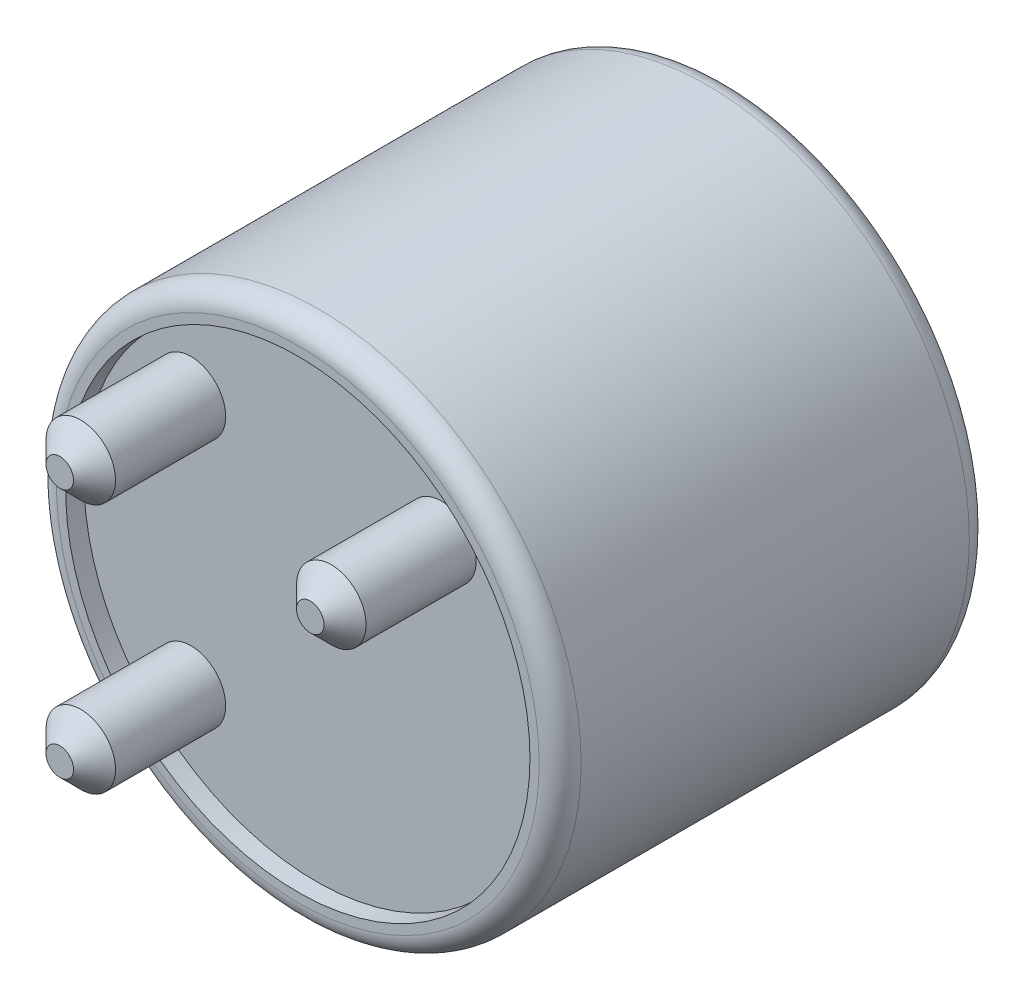
SolidWorks part; units mm, degrees
ref_plane "Спереди" through (0, 0, 0) normal (0, 0, 1) x (1, 0, 0)
ref_plane "Сверху" through (0, 0, 0) normal (0, 1, 0) x (1, 0, 0)
ref_plane "Справа" through (0, 0, 0) normal (1, 0, 0) x (0, 0, -1)
sketch "Эскиз1" plane through (0, 0, 0) normal (0, 0, 1) x (1, 0, 0)
  circle A0 centre (0, 0) radius 10
  dimension "D1" = 20
extrude "Бобышка-Вытянуть1" add sketch "Эскиз1" along normal blind 16.4
sketch "Эскиз2" plane through (0, 0, 16.4) normal (0, 0, 1) x (1, 0, 0)
  circle A0 centre (0, 0) radius 8.85
  dimension "D1" = 17.7
extrude "Вырез-Вытянуть1" cut sketch "Эскиз2" against normal blind 0.7
sketch "Эскиз3" plane through (0, 0, 15.7) normal (0, 0, 1) x (1, 0, 0)
  line L1 (4.775, -4.775) -> (-4.775, -4.775) construction
  line L2 (4.775, -4.775) -> (4.775, 4.775) construction
  line L3 (4.775, 4.775) -> (-4.775, 4.775) construction
  line L4 (-4.775, -4.775) -> (-4.775, 4.775) construction
  line L5 (4.775, -4.775) -> (-4.775, 4.775) construction
  line L6 (4.775, 4.775) -> (-4.775, -4.775) construction
  circle A0 centre (-4.775, 4.775) radius 1.325
  circle A1 centre (-4.775, -4.775) radius 1.325
  circle A2 centre (4.775, 4.775) radius 1.325
  point P0 (0, 0)
  dimension "D3" = 2.65
  dimension "D1" = 9.55
  dimension "D2" = 9.55
extrude "Бобышка-Вытянуть2" add sketch "Эскиз3" along normal blind 5
chamfer "Фаска1" distance 0.8 angle 45 3 edges at (6.1, 4.775, 20.7) (-3.45, -4.775, 20.7) (-3.45, 4.775, 20.7)
sketch "Эскиз4" plane through (0, 0, 0) normal (0, 0, -1) x (-1, 0, 0)
  circle A0 centre (0, 0) radius 8.05
  dimension "D1" = 16.1
extrude "Вырез-Вытянуть2" cut sketch "Эскиз4" against normal blind 0.4
fillet "Скругление1" radius 0.8 2 edges at (10, 0, 0) (10, 0, 16.4)
sketch "Эскиз5" plane through (0, 0, 0.4) normal (0, 0, -1) x (-1, 0, 0)
  circle A0 centre (0, 0) radius 7
  dimension "D1" = 14
extrude "Бобышка-Вытянуть3" add sketch "Эскиз5" along normal blind 0.2
